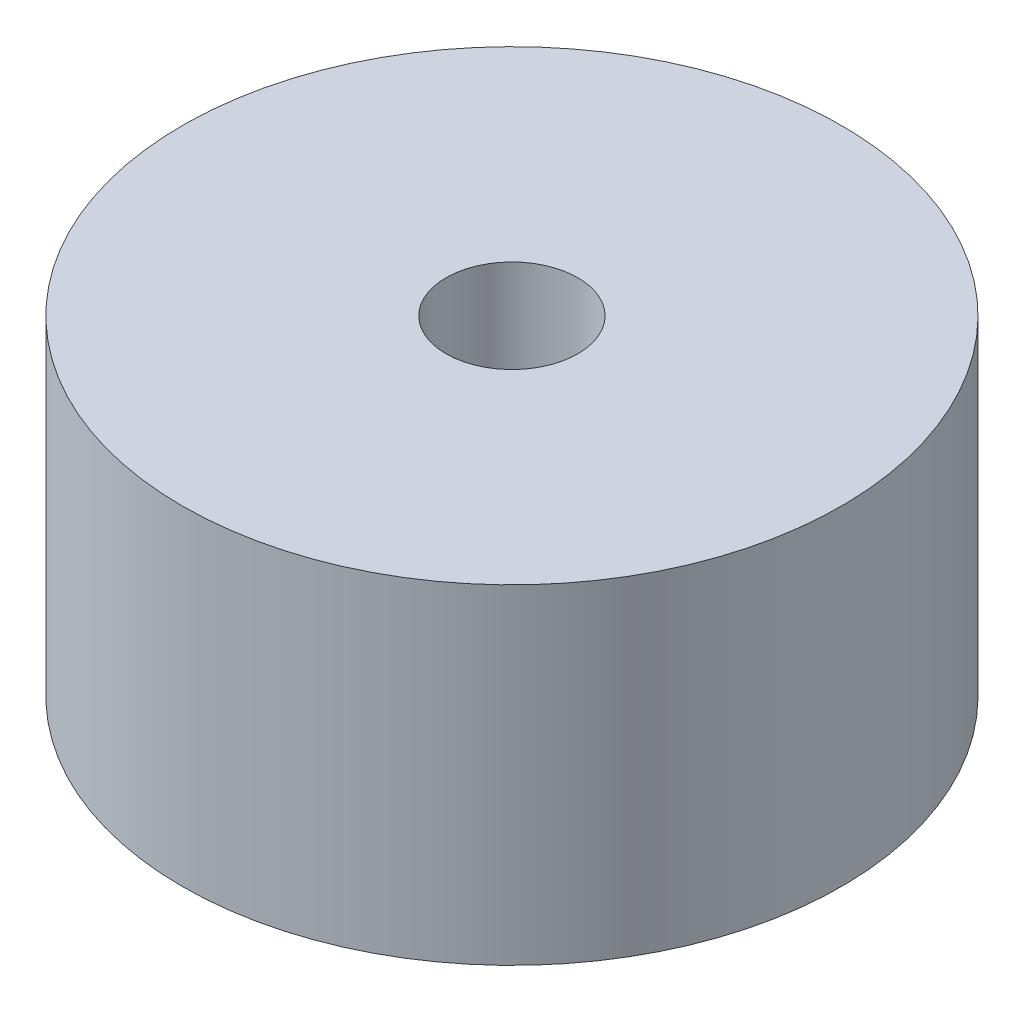
SolidWorks part; units mm, degrees
ref_plane "Front Plane" through (0, 0, 0) normal (0, 0, 1) x (1, 0, 0)
ref_plane "Top Plane" through (0, 0, 0) normal (0, 1, 0) x (1, 0, 0)
ref_plane "Right Plane" through (0, 0, 0) normal (1, 0, 0) x (0, 0, -1)
sketch "Sketch1" plane through (0, 0, 0) normal (0, 1, 0) x (1, 0, 0)
  circle A0 centre (0, 0) radius 50
  circle A1 centre (0, 0) radius 10
  dimension "D1" = 20
  dimension "D2" = 100
extrude "Boss-Extrude1" add sketch "Sketch1" along normal blind 50
